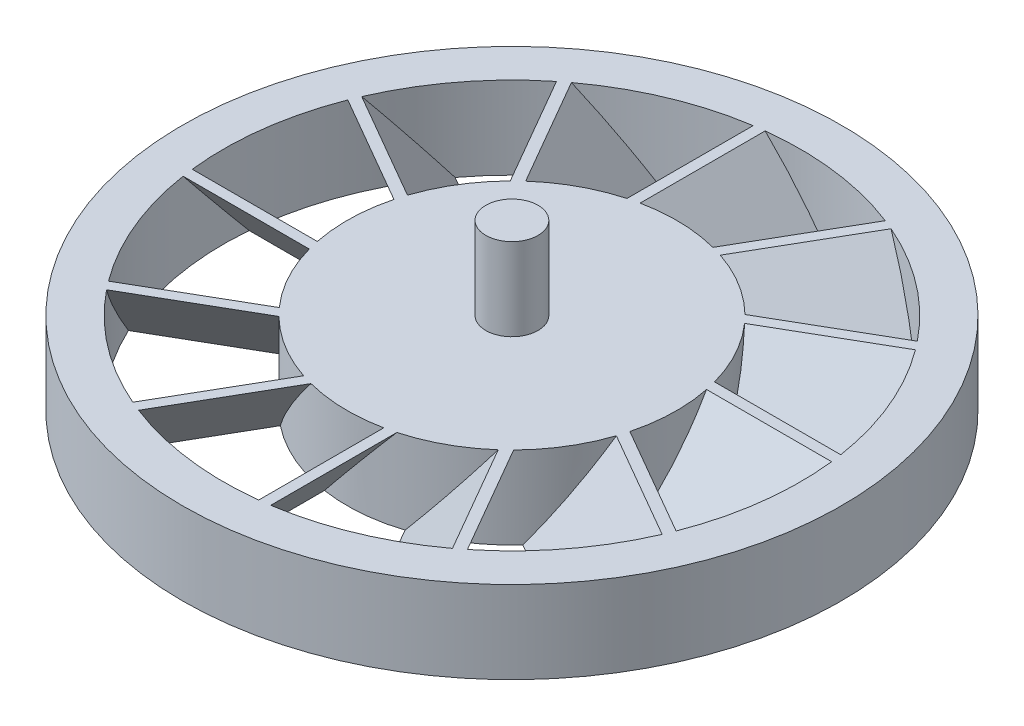
SolidWorks part; units mm, degrees
ref_plane "Front Plane" through (0, 0, 0) normal (0, 0, 1) x (1, 0, 0)
ref_plane "Top Plane" through (0, 0, 0) normal (0, 1, 0) x (1, 0, 0)
ref_plane "Right Plane" through (0, 0, 0) normal (1, 0, 0) x (0, 0, -1)
sketch "Sketch1" plane through (0, 0, 0) normal (0, 1, 0) x (1, 0, 0)
  circle A0 centre (0, 0) radius 20
  circle A1 centre (0, 0) radius 35
  circle A2 centre (0, 0) radius 40
  dimension "D1" = 40
  dimension "D2" = 70
  dimension "D3" = 80
extrude "Boss-Extrude1" add sketch "Sketch1" along normal blind 10
sketch "Sketch2" plane through (0, 0, 0) normal (0, 0, 1) x (1, 0, 0)
  line L0 (0, 85.4193) -> (0, -73.7814) construction
sketch "Sketch3" plane through (0, 0, 0) normal (1, 0, 0) x (0, 0, -1)
  line L0 (-40, 0) -> (40, 0) construction
  line L1 (-35, 10) -> (-20, 10) construction
  line L2 (-35, 10) -> (-35, 0) construction
  line L3 (-35, 0) -> (-20, 0) construction
  line L4 (-20, 10) -> (-20, 0) construction
  line L5 (20, 10) -> (-20, 10) construction
  line L6 (-20, 10) -> (-20, 0) construction
sketch "Sketch4" plane through (0, 0, 0) normal (1, 0, 0) x (0, 0, -1)
  line L0 (-4.2624, 0) -> (4.0314, 10)
  line L1 (-40, 0) -> (40, 0) construction
  line L2 (40, 10) -> (-40, 10) construction
  line L3 (-2.9787, 0) -> (5.3151, 10)
  line L4 (5.3151, 10) -> (4.0314, 10)
  line L5 (-4.2624, 0) -> (-2.9787, 0)
extrude "Boss-Extrude2" add sketch "Sketch4" against normal up to surface and the other way up to surface from offset 30
pattern_circular "CirPattern1" count 12 over 360 about axis through (0, 0, 0) along (0, 1, 0) of "Boss-Extrude2"
sketch "Sketch5" plane through (0, 10, 0) normal (0, 1, 0) x (1, 0, 0)
  circle A0 centre (0, 0) radius 3.1677
  dimension "D1" = 6.3355
extrude "Boss-Extrude3" add sketch "Sketch5" along normal blind 10
scale "Scale1" scale about origin uniform scaling yes scale factor 0.75
equation "\"D1@Sketch1\"= \"D3@Sketch1\" / 2"
equation "\"D2@Sketch1\"= \"D3@Sketch1\" * 7 / 8"
